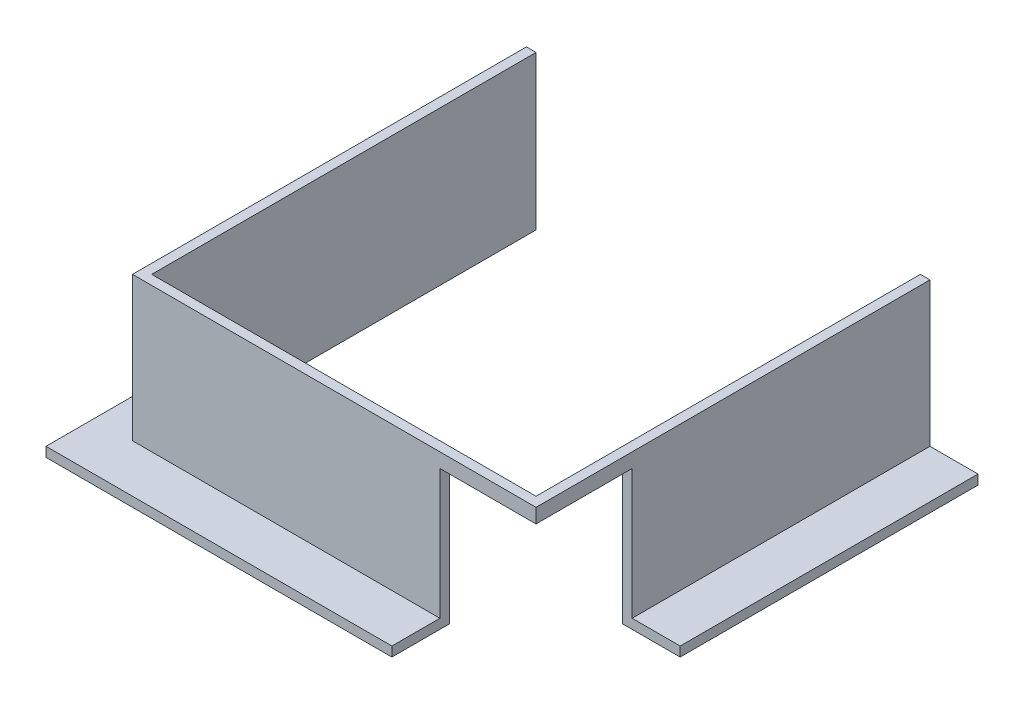
SolidWorks part; units mm, degrees
ref_plane "Front Plane" through (0, 0, 0) normal (0, 0, 1) x (1, 0, 0)
ref_plane "Top Plane" through (0, 0, 0) normal (0, 1, 0) x (1, 0, 0)
ref_plane "Right Plane" through (0, 0, 0) normal (1, 0, 0) x (0, 0, -1)
sketch "Sketch1" plane through (0, 0, 0) normal (0, 1, 0) x (1, 0, 0)
  line L0 (0, 0) -> (80, 0)
  line L1 (0, 0) -> (0, 80)
  line L2 (80, 0) -> (80, 80)
  line L3 (0, 80) -> (-2, 80)
  line L4 (-2, 80) -> (-2, -2)
  line L6 (80, -2) -> (-2, -2)
  line L7 (80, -2) -> (82, -2)
  line L8 (82, -2) -> (82, 80)
  line L9 (82, 80) -> (80, 80)
extrude "Boss-Extrude1" add sketch "Sketch1" along normal blind 30
sketch "Sketch2" plane through (82, 0, 0) normal (1, 0, 0) x (0, 0, -1)
  line L0 (-2, 0) -> (18, 0)
  line L1 (-2, 0) -> (80, 0) construction
  line L2 (-2, 0) -> (-2, 20)
  line L3 (-2, 30) -> (-2, 0) construction
  line L4 (-2, 20) -> (18, 20)
  line L5 (18, 20) -> (18, 0)
extrude "Cut-Extrude1" cut sketch "Sketch2" against normal blind 20
sketch "Sketch3" plane through (0, 0, 0) normal (0, -1, 0) x (1, 0, 0)
  line L0 (0, -80) -> (-10, -80)
  line L1 (-10, -80) -> (-10, 7.4129)
  line L3 (-10, 7.4129) -> (-10, 12)
  line L4 (92, 2) -> (92, 12)
  line L5 (-10, 12) -> (92, 12)
  line L6 (92, 2) -> (92, -80)
  line L7 (92, -80) -> (80, -80)
  line L8 (80, -80) -> (80, 0)
  line L9 (80, 0) -> (0, 0)
  line L10 (0, 0) -> (0, -80)
extrude "Boss-Extrude2" add sketch "Sketch3" along normal blind 2
sketch "Sketch4" plane through (92, 0, 0) normal (1, 0, 0) x (0, 0, -1)
  line L0 (18, 0) -> (18, -2)
  line L1 (80, -2) -> (-12, -2) construction
  line L2 (18, -2) -> (-12, -2)
  line L3 (-12, -2) -> (-12, 0)
  line L4 (-12, 0) -> (18, 0)
extrude "Cut-Extrude2" cut sketch "Sketch4" against normal blind 30
sketch "Sketch5" plane through (82, 0, 0) normal (1, 0, 0) x (0, 0, -1)
  line L0 (18, 20) -> (18, 27)
  line L1 (18, 27) -> (-2, 27)
  line L2 (-2, 30) -> (-2, 20) construction
  line L3 (-2, 27) -> (-2, 20)
  line L4 (-2, 20) -> (18, 20)
extrude "Cut-Extrude3" cut sketch "Sketch5" against normal blind 20
